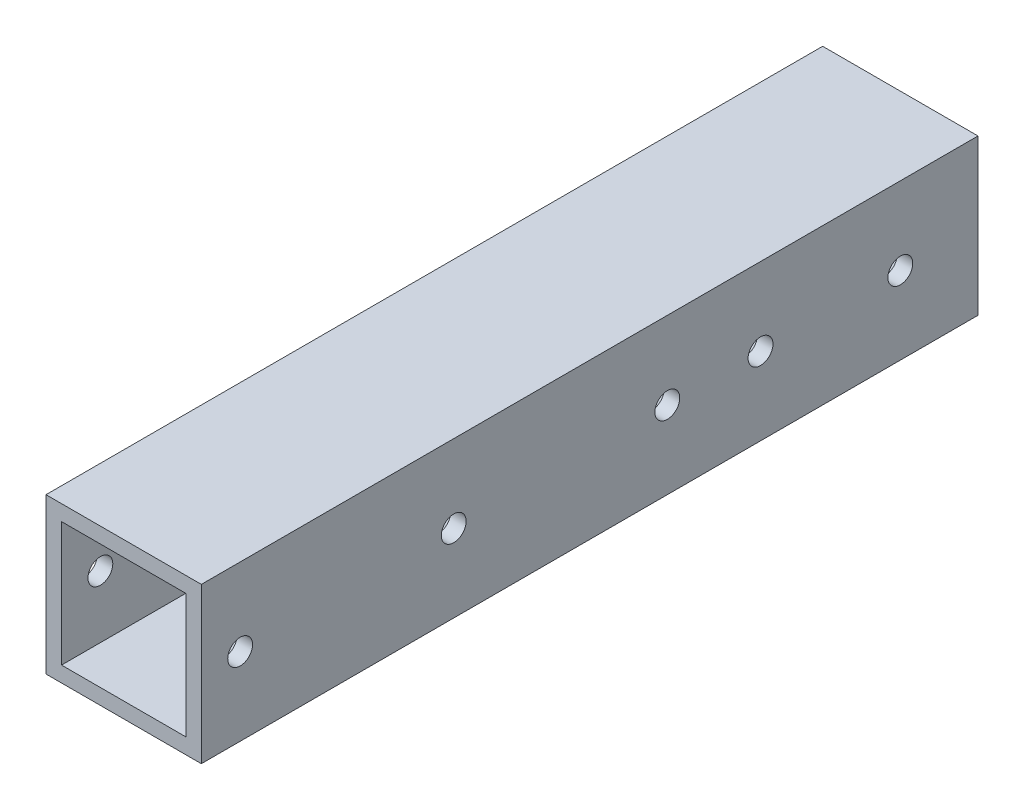
SolidWorks part; units mm, degrees
material "6061 合金"
ref_plane "前视基准面" through (0, 0, 0) normal (0, 0, 1) x (1, 0, 0)
ref_plane "上视基准面" through (0, 0, 0) normal (0, 1, 0) x (1, 0, 0)
ref_plane "右视基准面" through (0, 0, 0) normal (1, 0, 0) x (0, 0, -1)
other "Configuration Table"
sketch "草图1" plane through (0, 0, 0) normal (0, 0, 1) x (1, 0, 0)
  line L1 (0, 0) -> (20, 0)
  line L2 (0, 0) -> (0, 20)
  line L3 (0, 20) -> (20, 20)
  line L4 (20, 0) -> (20, 20)
  dimension "D1" = 20
  dimension "D2" = 20
extrude "拉伸-薄壁1" add sketch "草图1" along normal blind 100 thin thin type one direction reverse wall 2
sketch "草图2" plane through (0, 0, 0) normal (-1, 0, 0) x (0, 0, 1)
  line L0 (0, 10) -> (100, 10) construction
  line L1 (0, 20) -> (0, 0) construction
  line L2 (100, 20) -> (100, 0) construction
  circle A0 centre (10, 10) radius 1.6
  circle A2 centre (28, 10) radius 1.6
  dimension "D1" = 3.2
  dimension "D3" = 2
  dimension "D4" = 18
  dimension "D2" = 10
extrude "切除-拉伸1" cut sketch "草图2" against normal through all
sketch "草图3" plane through (0, 0, 0) normal (-1, 0, 0) x (0, 0, 1)
  line L0 (100, 10) -> (35, 10) construction
  line L1 (100, 20) -> (100, 0) construction
  circle A0 centre (67.5, 10) radius 1.6
  circle A1 centre (40, 10) radius 1.6
  circle A2 centre (95, 10) radius 1.6
  dimension "D2" = 3.2
  dimension "D3" = 5
  dimension "D4" = 5
  dimension "D1" = 65
extrude "切除-拉伸2" cut sketch "草图3" against normal through all
